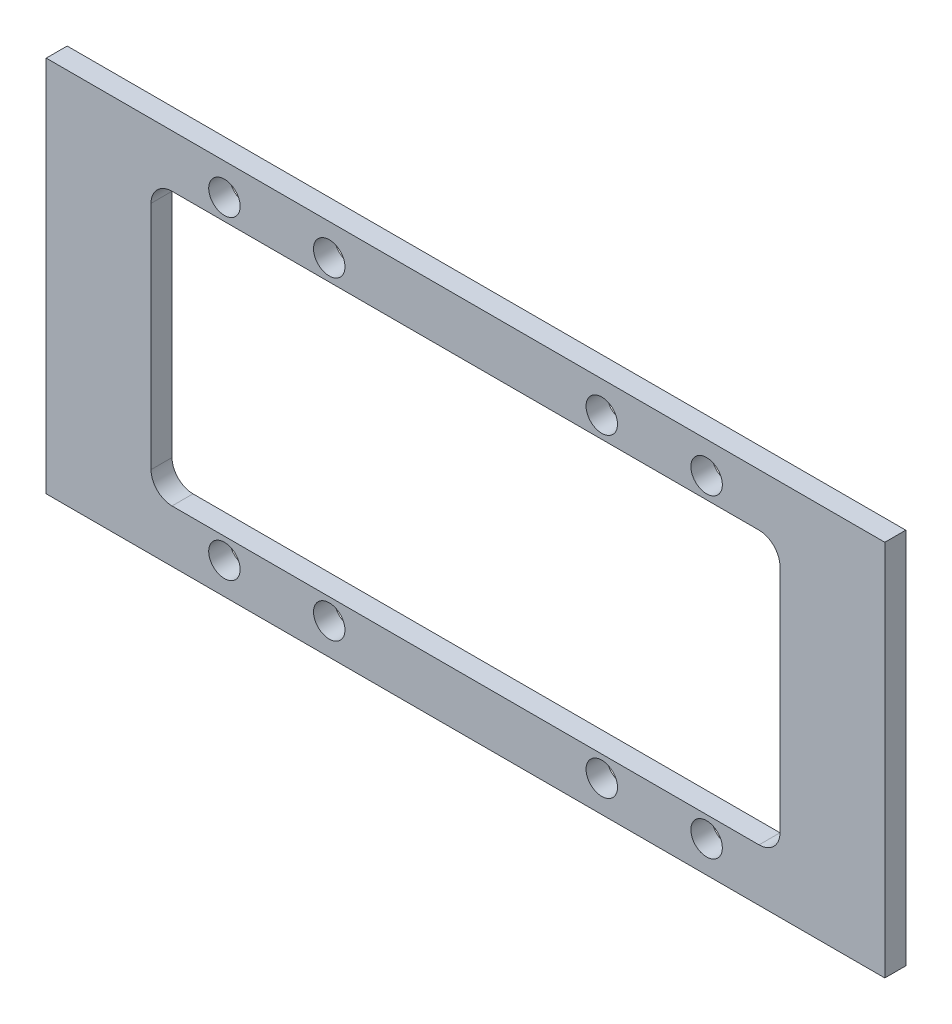
SolidWorks part; units mm, degrees
material "Thornel Mat VMA"
ref_plane "前视基准面" through (0, 0, 0) normal (0, 0, 1) x (1, 0, 0)
ref_plane "上视基准面" through (0, 0, 0) normal (0, 1, 0) x (1, 0, 0)
ref_plane "右视基准面" through (0, 0, 0) normal (1, 0, 0) x (0, 0, -1)
other "Configuration Table"
sketch "草图1" plane through (0, 0, 0) normal (0, 0, 1) x (1, 0, 0)
  line L1 (-40, 18) -> (40, 18)
  line L2 (-40, 18) -> (-40, -18)
  line L3 (-40, -18) -> (40, -18)
  line L4 (40, 18) -> (40, -18)
  line L5 (-40, 18) -> (40, -18) construction
  line L6 (-40, -18) -> (40, 18) construction
  point P0 (0, 0)
  dimension "D1" = 80
  dimension "D2" = 36
extrude "凸台-拉伸1" add sketch "草图1" along normal blind 2
sketch "草图2" plane through (0, 0, 2) normal (0, 0, 1) x (1, 0, 0)
  line L5 (-30, -8) -> (-30, -13)
  line L6 (-30, -13) -> (30, -13)
  line L7 (30, -13) -> (30, -8)
  line L8 (30, -8) -> (30, 8)
  line L9 (30, 8) -> (-30, 8)
  line L10 (-30, 8) -> (-30, -8)
  line L11 (-30, -8) -> (30, -8)
  line L12 (30, -8) -> (30, 8)
  line L14 (-30, 8) -> (-30, -8)
  line L16 (-30, 8) -> (-30, 13)
  line L17 (-30, 13) -> (30, 13)
  line L18 (30, 13) -> (30, 8)
  dimension "D2" = 5
  dimension "D1" = 10
extrude "切除-拉伸1" cut sketch "草图2" against normal blind 2
fillet "圆角2" radius 2 4 edges at (-30, 13, 1) (-30, -13, 1) (30, -13, 1) (30, 13, 1)
sketch "草图3" plane through (0, 0, 2) normal (0, 0, 1) x (1, 0, 0)
  circle A0 centre (23, -15) radius 1.5 construction
  circle A1 centre (13, -15) radius 1.5 construction
  circle A2 centre (-13, -15) radius 1.5 construction
  circle A3 centre (-23, -15) radius 1.5 construction
  circle A4 centre (23, 15) radius 1.5 construction
  circle A5 centre (13, 15) radius 1.5 construction
  circle A6 centre (-13, 15) radius 1.5 construction
  circle A7 centre (-23, 15) radius 1.5 construction
  circle A8 centre (23, -15) radius 1.5
  circle A9 centre (13, -15) radius 1.5
  circle A10 centre (-13, -15) radius 1.5
  circle A11 centre (-23, -15) radius 1.5
  circle A12 centre (23, 15) radius 1.5
  circle A13 centre (13, 15) radius 1.5
  circle A14 centre (-13, 15) radius 1.5
  circle A15 centre (-23, 15) radius 1.5
extrude "切除-拉伸2" cut sketch "草图3" against normal through all
